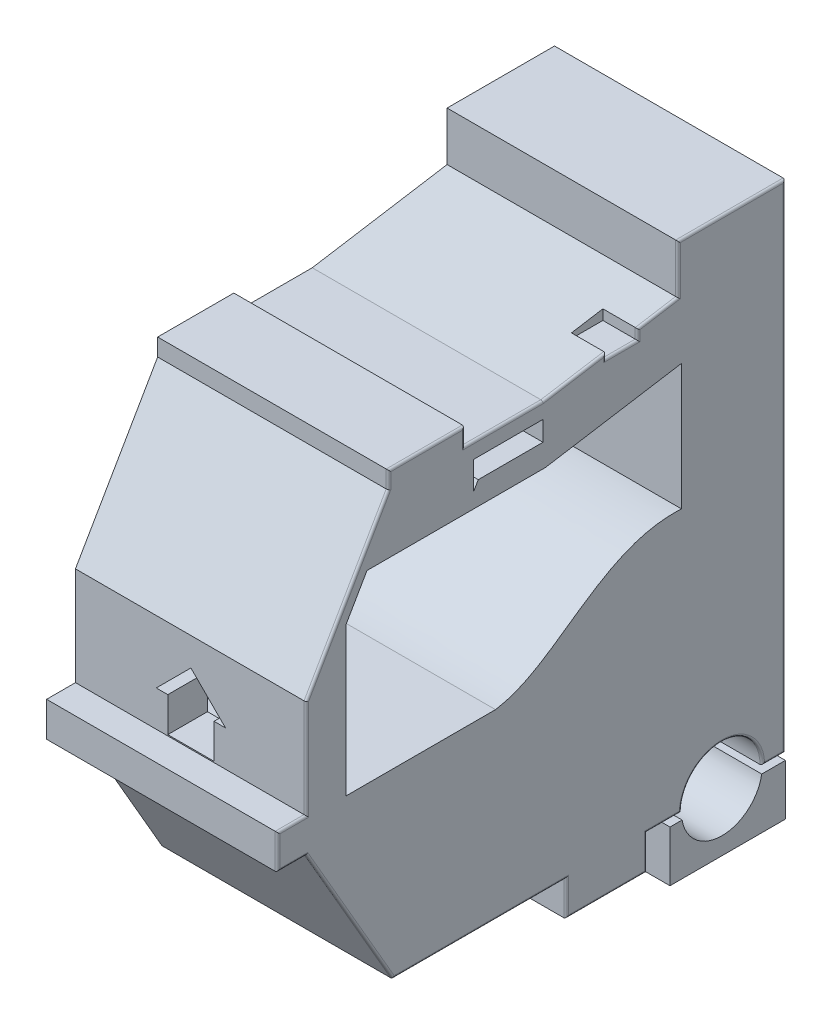
SolidWorks part; units mm, degrees
ref_plane "Front Plane" through (0, 0, 0) normal (0, 0, 1) x (1, 0, 0)
ref_plane "Top Plane" through (0, 0, 0) normal (0, 1, 0) x (1, 0, 0)
ref_plane "Right Plane" through (0, 0, 0) normal (1, 0, 0) x (0, 0, -1)
sketch "Sketch1" plane through (0, 0, 0) normal (1, 0, 0) x (0, 0, -1)
  line L0 (0, 12.1968) -> (0, -12.8938) construction
  line L1 (-36.8098, 0) -> (26.4845, 0) construction
  line L2 (3.5, 0) -> (5.5, 0)
  line L3 (5.5, 0) -> (5.5, 43)
  line L4 (5.5, 43) -> (-3.8067, 43)
  line L5 (-28.8806, 38.3581) -> (-22.2815, 38.3581)
  line L6 (-22.2815, 38.3581) -> (-22.2815, 36.8581)
  line L7 (-13.5, 0) -> (-28.5, 0)
  line L8 (-36, 12.9904) -> (-38.5, 12.9904)
  line L9 (-28.5, 0) -> (-36, 12.9904)
  line L10 (-38.5, 12.9904) -> (-38.5, 15.9904)
  line L11 (-13.5, 0) -> (-13.5, -3)
  line L12 (-13.5, -3) -> (-6.5, -3)
  line L13 (-6.5, -3) -> (-6.5, 0)
  line L14 (-6.5, 0) -> (-3.5, 0)
  line L15 (-38.5, 15.9904) -> (-36, 15.9904)
  line L16 (-36, 15.9904) -> (-36, 24.527)
  line L17 (-36, 24.527) -> (-28.8806, 36.8581)
  line L18 (-28.8806, 36.8581) -> (-28.8806, 38.3581)
  line L19 (-22.2815, 36.8581) -> (-15.4869, 36.8581)
  line L20 (-15.4869, 36.8581) -> (-3.8067, 38.7602)
  line L21 (-21.5137, 33.7517) -> (-21.5137, 33.0718)
  line L22 (-21.5137, 35.49) -> (-15.5, 35.49)
  line L23 (-21.5137, 35.49) -> (-21.5137, 33.7517)
  line L24 (-21.1095, 33.7718) -> (-15.5, 33.7718)
  line L25 (-15.5, 35.49) -> (-15.5, 33.7718)
  line L26 (-21.5137, 33.0718) -> (-21.1095, 33.7718)
  line L27 (-32.5615, 15.7718) -> (-32.5615, 28.6297)
  line L28 (-3.5, 33.6927) -> (-15.2954, 31.7718)
  line L29 (-15.2954, 31.7718) -> (-30.7474, 31.7718)
  line L30 (-3.5, 33.6927) -> (-3.5, 22.7718)
  line L31 (-32.5615, 15.7718) -> (-19.6131, 15.7718)
  line L32 (-3.8067, 43) -> (-3.8067, 38.7602)
  line L33 (-30.7474, 31.7718) -> (-32.5615, 28.6297)
  line L34 (-5.6518, -0.5917) -> (4.7646, -0.5917) construction
  line L35 (-3.4496, -0.5917) -> (-4.5, -0.5917)
  line L36 (-4.5, -0.5917) -> (-4.5, -5)
  line L37 (-4.5, -5) -> (5.5, -5)
  line L38 (5.5, -5) -> (5.5, -0.5917)
  line L39 (5.5, -0.5917) -> (3.4496, -0.5917)
  arc A0 (3.5, 0) -> (-3.5, 0) centre (0, 0) ccw
  arc A1 (-3.4496, -0.5917) -> (3.4496, -0.5917) centre (0, 0) ccw
  spline S0 degree 3 poles (-19.6131, 15.7718) (-17.6417, 16.0754) (-12.5725, 19.2272) (-7.9918, 23.044) (-3.5, 22.7718) knots 0 0 0 0 0.328342 1 1 1 1
  dimension "D1" = 3.5
  dimension "D2" = 3.5
  dimension "D3" = 43
  dimension "D7" = 5
  dimension "D37" = 17.8896
  dimension "D4" = 9.3067
  dimension "D5" = 2
  dimension "D6" = 2.0504
  dimension "D8" = 10
  dimension "D9" = 2
  dimension "D10" = 3
  dimension "D11" = 7
  dimension "D12" = 15
  dimension "D13" = 15
  dimension "D14" = 120
  dimension "D15" = 2.5
  dimension "D16" = 2.5
  dimension "D17" = 3
  dimension "D18" = 150
  dimension "D19" = 14.2388
  dimension "D20" = 6.5991
  dimension "D21" = 6.7947
  dimension "D22" = 11.834
  dimension "D23" = 6.1419
  dimension "D24" = 1.5
  dimension "D25" = 1.3681
  dimension "D26" = 6.0137
  dimension "D27" = 1.7182
  dimension "D28" = 3.4385
  dimension "D29" = 180
  dimension "D30" = 0.9264
  dimension "D31" = 7
  dimension "D32" = 16
  dimension "D33" = 10.9208
  dimension "D34" = 180
  dimension "D35" = 3.6283
  dimension "D36" = 15.452
  dimension "D38" = 12.9485
  dimension "D39" = 2
  dimension "D40" = 30
  dimension "D41" = 21
  dimension "D42" = 1.5
  dimension "D43" = 0.7
  dimension "D44" = 7.1219
  dimension "D45" = 10.8655
  dimension "D46" = 13.7278
  dimension "D47" = 0.7412
  dimension "D48" = 2.445
  dimension "D49" = 4.9777
extrude "Boss-Extrude4" add sketch "Sketch1" along normal blind 20
sketch "Sketch2" plane through (20, 0, 0) normal (1, 0, 0) x (0, 0, -1)
  line L1 (-7.3099, 37.3156) -> (-10.0367, 37.3156)
  line L2 (-7.3099, 37.3156) -> (-7.3099, 38.4238)
  line L3 (-7.3099, 38.4238) -> (-10.0367, 38.4238)
  line L4 (-10.0367, 37.3156) -> (-10.0367, 38.4238)
extrude "Cut-Extrude1" cut sketch "Sketch2" against normal blind 3
sketch "Sketch3" plane through (0, 0, 36) normal (0, 0, 1) x (1, 0, 0)
  line L0 (8, 16.0904) -> (12, 16.0904)
  line L1 (12, 16.0904) -> (12, 19.0904)
  line L2 (12, 19.0904) -> (13, 19.0904)
  line L3 (13, 19.0904) -> (10, 22.0904)
  line L4 (10, 22.0904) -> (7, 19.0904)
  line L5 (7, 19.0904) -> (8, 19.0904)
  line L6 (8, 19.0904) -> (8, 16.0904)
  line L7 (20, 24.527) -> (20, 15.9904) construction
  line L8 (10, 22.8696) -> (10, 15.4235) construction
  line L10 (20, 15.9904) -> (0, 15.9904) construction
  line L11 (0, 24.527) -> (0, 15.9904) construction
  dimension "D1" = 4
  dimension "D2" = 3
  dimension "D3" = 0.1
  dimension "D4" = 6
extrude "Cut-Extrude2" cut sketch "Sketch3" against normal up to surface (3.4385 mm away) up to face at (10, 22.2008, 32.5615)
fillet "Fillet3" radius 0.2 25 edges at (20, 37.5306, 10.0367) (20, 37.7526, 7.3099) (20, 37.3156, 8.6733) (20, 37.3019, 12.7618) (20, 36.8581, 18.8842) (20, 37.6081, 22.2815) (20, 38.3581, 25.581) (20, 37.6081, 28.8806) (20, 38.4749, 5.5583) (20, 40.8801, 3.8067) (20, 43, -0.8466) (20, 21.5, -5.5) (20, 0, -4.5) (20, 3.5, 0) (20, 0, 5) (20, -1.5, 6.5) (20, -3, 10) (20, -1.5, 13.5) (20, 0, 21) (20, 6.4952, 32.25) (20, 12.9904, 37.25) (20, 15.9904, 37.25) (20, 14.4904, 38.5) (20, 20.2587, 36) (20, 30.6925, 32.4403)
sketch "Sketch5" plane through (0, 0, 0) normal (-1, 0, 0) x (0, 0, 1)
  line L1 (2.2291, 9.1682) -> (17.4868, 9.1682)
  line L2 (2.2291, 9.1682) -> (2.2291, 13.0209)
  line L3 (2.2291, 13.0209) -> (17.4868, 13.0209)
  line L4 (17.4868, 9.1682) -> (17.4868, 13.0209)
extrude "Boss-Extrude6" add sketch "Sketch5" along normal blind 0.5
